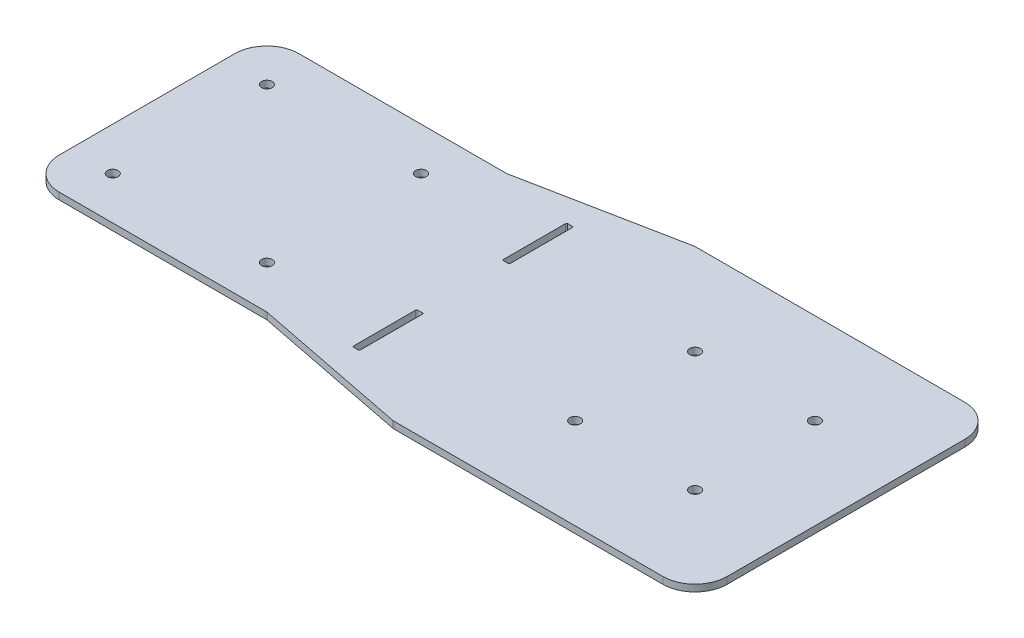
SolidWorks part; units mm, degrees
ref_plane "Front Plane" through (0, 0, 0) normal (0, 0, 1) x (1, 0, 0)
ref_plane "Top Plane" through (0, 0, 0) normal (0, 1, 0) x (1, 0, 0)
ref_plane "Right Plane" through (0, 0, 0) normal (1, 0, 0) x (0, 0, -1)
sketch "Sketch1" plane through (0, 0, 0) normal (0, 1, 0) x (1, 0, 0)
  line L0 (0, 0) -> (200, 0) construction
  line L1 (56, 56) -> (129.5, 70.5)
  line L2 (129.5, 70.5) -> (270.5, 70.5)
  line L3 (129.5, 70.5) -> (129.5, -70.5) construction
  line L4 (129.5, -70.5) -> (270.5, -70.5)
  line L5 (270.5, 70.5) -> (270.5, -70.5)
  line L6 (129.5, 70.5) -> (270.5, -70.5) construction
  line L7 (129.5, -70.5) -> (270.5, 70.5) construction
  line L8 (-56, 56) -> (56, 56)
  line L9 (-56, 56) -> (-56, -56)
  line L10 (-56, -56) -> (56, -56)
  line L11 (56, 56) -> (56, -56) construction
  line L12 (-56, 56) -> (56, -56) construction
  line L13 (-56, -56) -> (56, 56) construction
  line L14 (56, -56) -> (129.5, -70.5)
  dimension "D1" = 200
  dimension "D2" = 141
  dimension "D3" = 112
extrude "Boss-Extrude1" add sketch "Sketch1" along normal blind 3.175
sketch "Sketch5" plane through (0, 3.175, 0) normal (0, 1, 0) x (1, 0, 0)
  line L0 (-56, 0) -> (270.5, 0) construction
  line L1 (-56, 56) -> (-56, -56) construction
  line L2 (270.5, -70.5) -> (270.5, 70.5) construction
  line L3 (200, 70.5) -> (200, -70.5) construction
  line L4 (270.5, 70.5) -> (129.5, 70.5) construction
  line L5 (129.5, -70.5) -> (270.5, -70.5) construction
  circle A1 centre (172, 28) radius 2.5
  circle A2 centre (228, 28) radius 2.5
  circle A3 centre (228, -28) radius 2.5
  circle A4 centre (172, -28) radius 2.5
  point P0 (200, 0)
  dimension "D1" = 200
  dimension "D2" = 5
  dimension "D3" = 28
  dimension "D4" = 28
extrude "Cut-Extrude2" cut sketch "Sketch5" against normal through all
sketch "Sketch6" plane through (0, 3.175, 0) normal (0, 1, 0) x (1, 0, 0)
  line L0 (-56, 0) -> (270.5, 0) construction
  line L1 (-56, 56) -> (-56, -56) construction
  line L2 (270.5, -70.5) -> (270.5, 70.5) construction
  line L3 (93.2, 20.5) -> (93.2, 49.5)
  line L4 (90.5, -20) -> (92.7, -20)
  line L5 (90, -20.5) -> (90, -49.5)
  line L6 (90.5, -50) -> (92.7, -50)
  line L7 (93.2, -20.5) -> (93.2, -49.5)
  line L8 (90.5, 50) -> (92.7, 50)
  line L9 (90, 20.5) -> (90, 49.5)
  line L10 (90.5, 20) -> (92.7, 20)
  arc A0 (90.5, -50) -> (90, -49.5) centre (90.5, -49.5) cw
  arc A1 (92.7, -50) -> (93.2, -49.5) centre (92.7, -49.5) ccw
  arc A2 (90, -20.5) -> (90.5, -20) centre (90.5, -20.5) cw
  arc A3 (93.2, -20.5) -> (92.7, -20) centre (92.7, -20.5) ccw
  arc A4 (93.2, 20.5) -> (92.7, 20) centre (92.7, 20.5) cw
  arc A5 (90, 20.5) -> (90.5, 20) centre (90.5, 20.5) ccw
  arc A6 (92.7, 50) -> (93.2, 49.5) centre (92.7, 49.5) cw
  arc A7 (90.5, 50) -> (90, 49.5) centre (90.5, 49.5) ccw
  point P13 (90, -50)
  point P16 (93.2, -50)
  point P19 (90, -20)
  point P34 (90, 20)
  point P35 (93.2, 50)
  point P36 (90, 50)
  dimension "D5" = 0.5
  dimension "D1" = 30
  dimension "D2" = 3.2
  dimension "D3" = 90
  dimension "D4" = 20
extrude "Cut-Extrude3" cut sketch "Sketch6" against normal through all
fillet "Fillet1" radius 15 4 edges at (-56, 1.5875, 56) (-56, 1.5875, -56) (270.5, 1.5875, -70.5) (270.5, 1.5875, 70.5)
fillet "Fillet2" radius 5 4 edges at (129.5, 1.5875, 70.5) (56, 1.5875, 56) (129.5, 1.5875, -70.5) (56, 1.5875, -56)
sketch "Sketch7" plane through (0, 3.175, 0) normal (0, 1, 0) x (1, 0, 0)
  line L0 (0, 56) -> (0, -56) construction
  line L1 (55.5115, 56) -> (-41, 56) construction
  line L2 (-41, -56) -> (55.5115, -56) construction
  line L3 (-56, 0) -> (270.5, 0) construction
  line L4 (-56, 41) -> (-56, -41) construction
  line L5 (270.5, -55.5) -> (270.5, 55.5) construction
  circle A0 centre (-36, 36) radius 2.5
  circle A1 centre (36, 36) radius 2.5
  circle A2 centre (-36, -36) radius 2.5
  circle A3 centre (36, -36) radius 2.5
  dimension "D3" = 5
  dimension "D1" = 36
  dimension "D2" = 36
extrude "Cut-Extrude4" cut sketch "Sketch7" against normal through all
equation "\"Elevator Diameter\"= 135mm"
equation "\"Plate Thickness\"= 0.125in"
equation "\"Pivot to Pivot Distance\"= 200mm"
equation "\"D1@Sketch1\"=\"Pivot to Pivot Distance\""
equation "\"Extra Spacing\"= 3mm"
equation "\"D2@Sketch1\"=\"Elevator Diameter\"+\"Extra Spacing\"*2"
equation "\"Servo Size\"= 40mm"
equation "\"D1@Boss-Extrude1\"=\"Plate Thickness\""
equation "\"D1@Sketch5\"=\"Pivot to Pivot Distance\""
